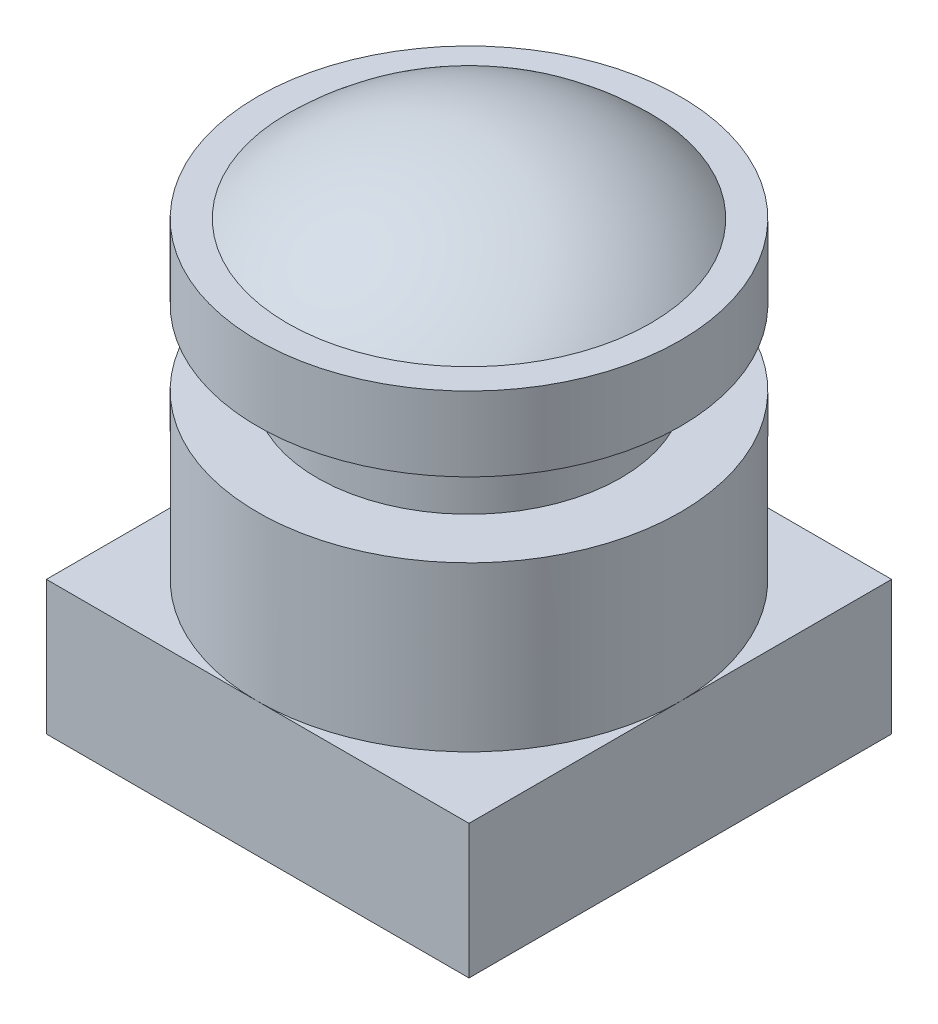
SolidWorks part; units mm, degrees
ref_plane "Front Plane" through (0, 0, 0) normal (0, 0, 1) x (1, 0, 0)
ref_plane "Top Plane" through (0, 0, 0) normal (0, 1, 0) x (1, 0, 0)
ref_plane "Right Plane" through (0, 0, 0) normal (1, 0, 0) x (0, 0, -1)
sketch "Sketch2" plane through (0, 0, 0) normal (0, 0, 1) x (1, 0, 0)
  line L0 (0, 0) -> (0, 13)
  line L1 (0, 13) -> (-2.663, 13) construction
  line L2 (6.1, 10.5) -> (7.1, 10.5)
  line L3 (7.1, 10.5) -> (7.1, 8)
  line L4 (7.1, 8) -> (5.1, 8)
  line L5 (5.1, 8) -> (5.1, 5.5)
  line L6 (5.1, 5.5) -> (7.1, 5.5)
  line L7 (7.1, 5.5) -> (7.1, 0)
  line L8 (7.1, 0) -> (0, 0)
  arc A0 (0, 13) -> (6.1, 10.5) centre (0, 4.308) cw
  point P10 (0, 0)
  point P13 (0, 0.2553)
  point P14 (5.1669, 10.5735)
  dimension "D1" = 7.1
  dimension "D2" = 2.5
  dimension "D3" = 2.5
  dimension "D4" = 2.5
  dimension "D5" = 2
  dimension "D6" = 1
  dimension "D7" = 5.5
revolve "Revolve1" add sketch "Sketch2" angle 360 about L0
sketch "Sketch3" plane through (0, 0, 0) normal (0, 1, 0) x (1, 0, 0)
  line L1 (-7.1, 7.1) -> (7.1, 7.1)
  line L2 (-7.1, 7.1) -> (-7.1, -7.1)
  line L3 (-7.1, -7.1) -> (7.1, -7.1)
  line L4 (7.1, 7.1) -> (7.1, -7.1)
  line L5 (-7.1, 7.1) -> (7.1, -7.1) construction
  line L6 (-7.1, -7.1) -> (7.1, 7.1) construction
  point P0 (0, 0)
  dimension "D1" = 14.2
extrude "Boss-Extrude1" add sketch "Sketch3" against normal blind 4.5
